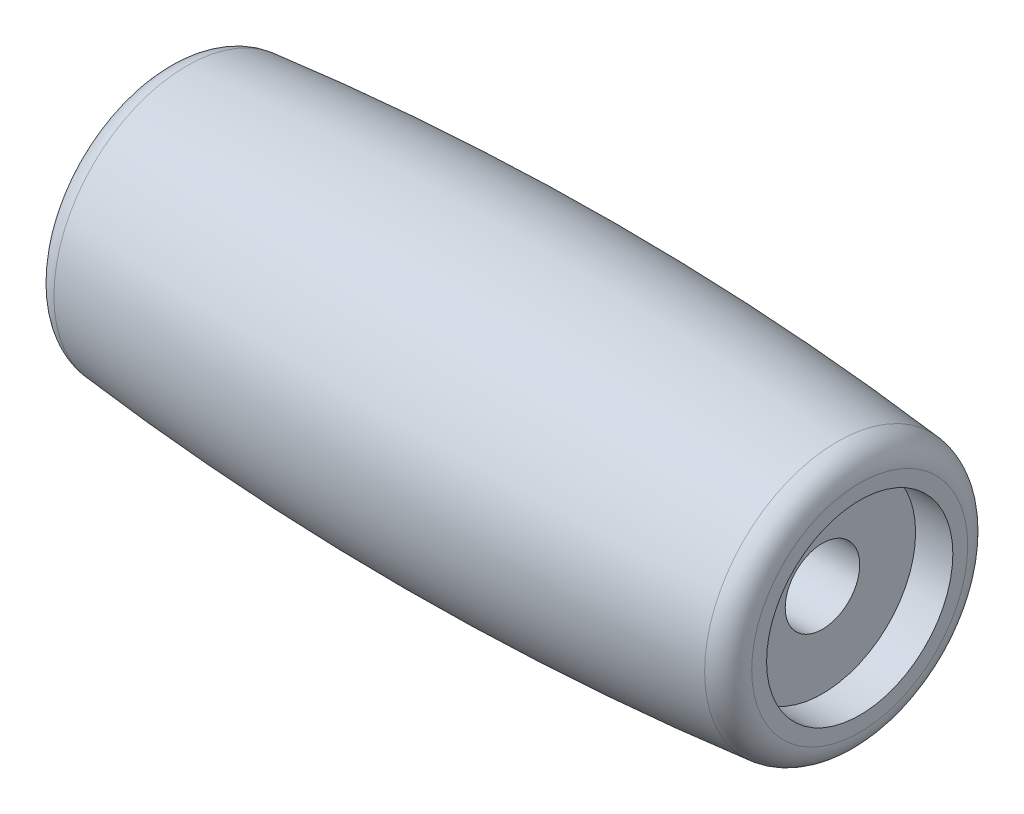
SolidWorks part; units mm, degrees
ref_plane "Front Plane" through (0, 0, 0) normal (0, 0, 1) x (1, 0, 0)
ref_plane "Top Plane" through (0, 0, 0) normal (0, 1, 0) x (1, 0, 0)
ref_plane "Right Plane" through (0, 0, 0) normal (1, 0, 0) x (0, 0, -1)
sketch "Sketch1" plane through (0, 0, 0) normal (0, 0, 1) x (1, 0, 0)
  line L0 (0, 0) -> (4706.0091, 0) construction
  line L1 (-14, 3.75) -> (-12.5, 3.75)
  line L2 (-12.5, 3.75) -> (-12.5, 1.5)
  line L3 (-12.5, 1.5) -> (12.5, 1.5)
  line L4 (12.5, 1.5) -> (12.5, 3.75)
  line L5 (12.5, 3.75) -> (14, 3.75)
  line L6 (0, 0) -> (0, -4706.0091) construction
  line L7 (-14, 3.75) -> (-14, 5.25)
  line L8 (14, 3.75) -> (14, 5.25)
  arc A0 (-14, 5.25) -> (14, 5.25) centre (0, -125.0417) cw
  point P14 (0, 6)
  dimension "D1" = 28
  dimension "D2" = 1.5
  dimension "D3" = 3.75
  dimension "D4" = 1.5
  dimension "D5" = 1.5
  dimension "D6" = 6
revolve "Revolve1" add sketch "Sketch1" angle 360 about L0
fillet "Fillet1" radius 1 2 edges at (14, 0, 5.25) (-14, 0, 5.25)
